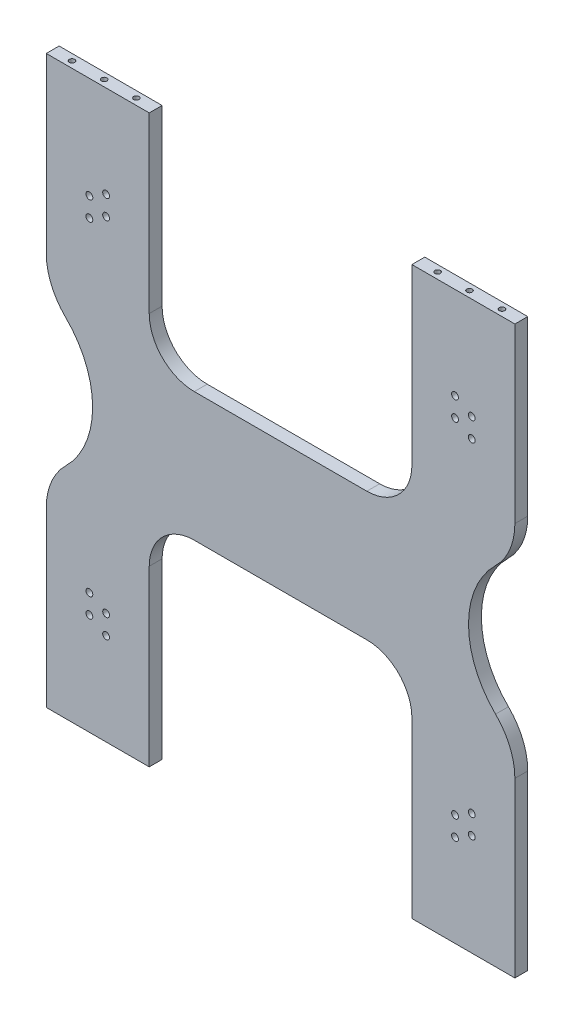
SolidWorks part; units mm, degrees
material "ABS"
ref_plane "Alzado" through (0, 0, 0) normal (0, 0, 1) x (1, 0, 0)
ref_plane "Planta" through (0, 0, 0) normal (0, 1, 0) x (1, 0, 0)
ref_plane "Vista lateral" through (0, 0, 0) normal (1, 0, 0) x (0, 0, -1)
sketch "Croquis1" plane through (0, 0, 0) normal (0, 0, 1) x (1, 0, 0)
  line L0 (0, -445.6503) -> (0, 445.6503) construction
  line L1 (0, 0) -> (589.6913, 0) construction
  line L2 (-67.025, 50) -> (67.025, 50)
  line L3 (102.025, 85) -> (102.025, 220)
  line L4 (102.025, 220) -> (182.025, 220)
  line L5 (182.025, 220) -> (182.025, 85.7143)
  line L6 (-182.025, 220) -> (-182.025, 85.7143)
  line L7 (-102.025, 220) -> (-182.025, 220)
  line L8 (-102.025, 85) -> (-102.025, 220)
  line L9 (-102.025, -85) -> (-102.025, -220)
  line L10 (-102.025, -220) -> (-182.025, -220)
  line L11 (-182.025, -220) -> (-182.025, -85.7143)
  line L12 (182.025, -220) -> (182.025, -85.7143)
  line L13 (102.025, -220) -> (182.025, -220)
  line L14 (102.025, -85) -> (102.025, -220)
  line L15 (-67.025, -50) -> (67.025, -50)
  arc A0 (67.025, 50) -> (102.025, 85) centre (67.025, 85) ccw
  arc A1 (182.025, 85.7143) -> (167.0177, 50) centre (132.025, 85.7143) cw
  arc A2 (167.0177, 50) -> (167.0177, -50) centre (216.0075, 0) ccw
  arc A3 (-167.0177, 50) -> (-167.0177, -50) centre (-216.0075, 0) cw
  arc A4 (-182.025, 85.7143) -> (-167.0177, 50) centre (-132.025, 85.7143) ccw
  arc A5 (-67.025, 50) -> (-102.025, 85) centre (-67.025, 85) cw
  arc A6 (-67.025, -50) -> (-102.025, -85) centre (-67.025, -85) ccw
  arc A7 (-182.025, -85.7143) -> (-167.0177, -50) centre (-132.025, -85.7143) cw
  arc A8 (182.025, -85.7143) -> (167.0177, -50) centre (132.025, -85.7143) ccw
  arc A9 (67.025, -50) -> (102.025, -85) centre (67.025, -85) cw
  point P39 (0, 50)
  point P54 (0, -50)
  dimension "D4" = 50
  dimension "D5" = 70
  dimension "D6" = 35
  dimension "D1" = 80
  dimension "D2" = 440
  dimension "D3" = 364.05
  dimension "D7" = 100
extrude "Saliente-Extruir1" add sketch "Croquis1" along normal blind 10
sketch "Croquis2" plane through (0, 220, 0) normal (0, 1, 0) x (1, 0, 0)
  line L0 (-102.025, -10) -> (-182.025, -10) construction
  line L1 (0, 0) -> (0, -10) construction
  line L2 (67.025, -10) -> (-67.025, -10) construction
  line L3 (-182.025, -10) -> (-182.025, 0) construction
  point P6 (-142.025, -5)
  point P7 (167.025, -5)
  point P8 (-117.025, -5)
  point P9 (-167.025, -5)
  point P11 (117.025, -5)
  point P14 (0, 0)
  point P15 (142.025, -5)
  point P16 (0, 0)
  point P17 (0, 0)
  point P18 (0, 0)
  point P19 (0, 0)
  point P20 (0, 0)
  dimension "D1" = 15
  dimension "D2" = 5
  dimension "D3" = 25
  dimension "D4" = 25
  dimension "D5" = 25
  dimension "D6" = 25
  dimension "D7" = 117.025
hole_wizard "Perforador para roscar para macho de roscar para M5x0.81" positions "Croquis3D2" profile "Croquis3" hole size "M5x0.8" standard "Ansi Metric"
sketch3d "Croquis3D2"
  point P0 (-167.025, 220, 5)
  point P3 (-117.025, 220, 5)
  point P6 (-271.0773, 0, -42.2427)
  point P8 (-142.025, 220, 5)
sketch "Croquis3" plane through (-167.025, 220, 5) normal (1, 0, 0) x (0, 0, 1)
  line L0 (0, 0) -> (0, 76.2618)
  line L1 (0, 76.2618) -> (2.1, 75)
  line L2 (2.1, 75) -> (2.1, 0)
  line L5 (2.1, 0) -> (0, 0)
  line L10 (0, 76.2618) -> (-2.1, 75) construction
  line L11 (0, -6.35) -> (0, 107.95) construction
  dimension "Diámetro de taladro" = 4.2
  dimension "Profundidad de taladro" = 75
  dimension "Ángulo de perforador" = 118
hole_wizard "Perforador para roscar para macho de roscar para M5x0.82" positions "Croquis3D4" profile "Croquis5" hole size "M5x0.8" standard "Ansi Metric"
sketch3d "Croquis3D4"
  point P0 (117.025, 220, 5)
  point P3 (167.025, 220, 5)
  point P6 (141.9, 220, 5.1379)
sketch "Croquis5" plane through (117.025, 220, 5) normal (1, 0, 0) x (0, 0, 1)
  line L0 (0, 0) -> (0, 76.2618)
  line L1 (0, 76.2618) -> (2.1, 75)
  line L2 (2.1, 75) -> (2.1, 0)
  line L5 (2.1, 0) -> (0, 0)
  line L10 (0, 76.2618) -> (-2.1, 75) construction
  line L11 (0, -6.35) -> (0, 107.95) construction
  dimension "Diámetro de taladro" = 4.2
  dimension "Profundidad de taladro" = 75
  dimension "Ángulo de perforador" = 118
mirror "Simetría1" about plane through (0, 0, 0) normal (0, 1, 0) of "Perforador para roscar para macho de roscar para M5x0.82", "Perforador para roscar para macho de roscar para M5x0.81"
sketch "Croquis6" plane through (0, 0, 0) normal (0, 0, -1) x (-1, 0, 0)
  line L0 (-219.6532, -133.5) -> (279.6893, -133.5) construction
  line L3 (-142.025, -220) -> (-142.025, 252.46) construction
  line L4 (-102.025, -220) -> (-182.025, -220) construction
  line L5 (-148.5202, -141) -> (-148.5202, -126) construction
  line L6 (-148.5202, -126) -> (-135.5298, -133.5) construction
  line L7 (-135.5298, -133.5) -> (-148.5202, -141) construction
  line L8 (-148.5202, -133.5) -> (-135.5298, -133.5) construction
  line L9 (-142.025, -137.25) -> (-148.5202, -126) construction
  line L10 (-148.5202, -141) -> (-135.5298, -148.5) construction
  line L11 (-135.5298, -148.5) -> (-135.5298, -133.5) construction
  line L12 (-142.025, -144.75) -> (-135.5298, -133.5) construction
  line L13 (-148.5202, -126) -> (-135.5298, -126) construction
  line L14 (-142.025, -126) -> (-142.025, -159.2966) construction
  point P16 (-142.025, -126)
  point P17 (-144.1901, -133.5)
  dimension "D1" = 15
  dimension "D2" = 86.5
  dimension "D3" = 79
hole_wizard "Refrentado para tornillo tapón con cabeza plana de clavija de M51" positions "Croquis3D5" profile "Croquis7" countersink size "M5" standard "Ansi Metric" end condition up to next
sketch3d "Croquis3D5"
  point P0 (148.5202, -141, 0)
  point P3 (135.5298, -133.5, 0)
  point P6 (135.5298, -148.5, 0)
  point P9 (148.5202, -126, 0)
sketch "Croquis7" plane through (148.5202, -141, 0) normal (1, 0, 0) x (0, 1, 0)
  line L0 (0, 0) -> (0, 10.001)
  line L1 (0, 10.001) -> (2.65, 10.001)
  line L2 (2.65, 10.001) -> (2.65, 2.95)
  line L3 (2.65, 2.95) -> (5.6, 0)
  line L5 (5.6, 0) -> (0, 0)
  line L6 (-2.65, 2.95) -> (-5.6, 0) construction
  line L11 (0, -6.35) -> (0, 107.95) construction
  dimension "Diámetro de taladro hasta el siguiente" = 5.3
  dimension "Profundidad de taladro hasta el siguiente" = 10.001
  dimension "Diámetro de avellanado cercano" = 11.2
  dimension "Ángulo de avellanado cercano" = 90
mirror "Simetría2" about plane through (0, 0, 0) normal (0, 1, 0) of "Refrentado para tornillo tapón con cabeza plana de clavija de M51"
mirror "Simetría3" about plane through (0, 0, 0) normal (1, 0, 0) of "Simetría2", "Refrentado para tornillo tapón con cabeza plana de clavija de M51"
